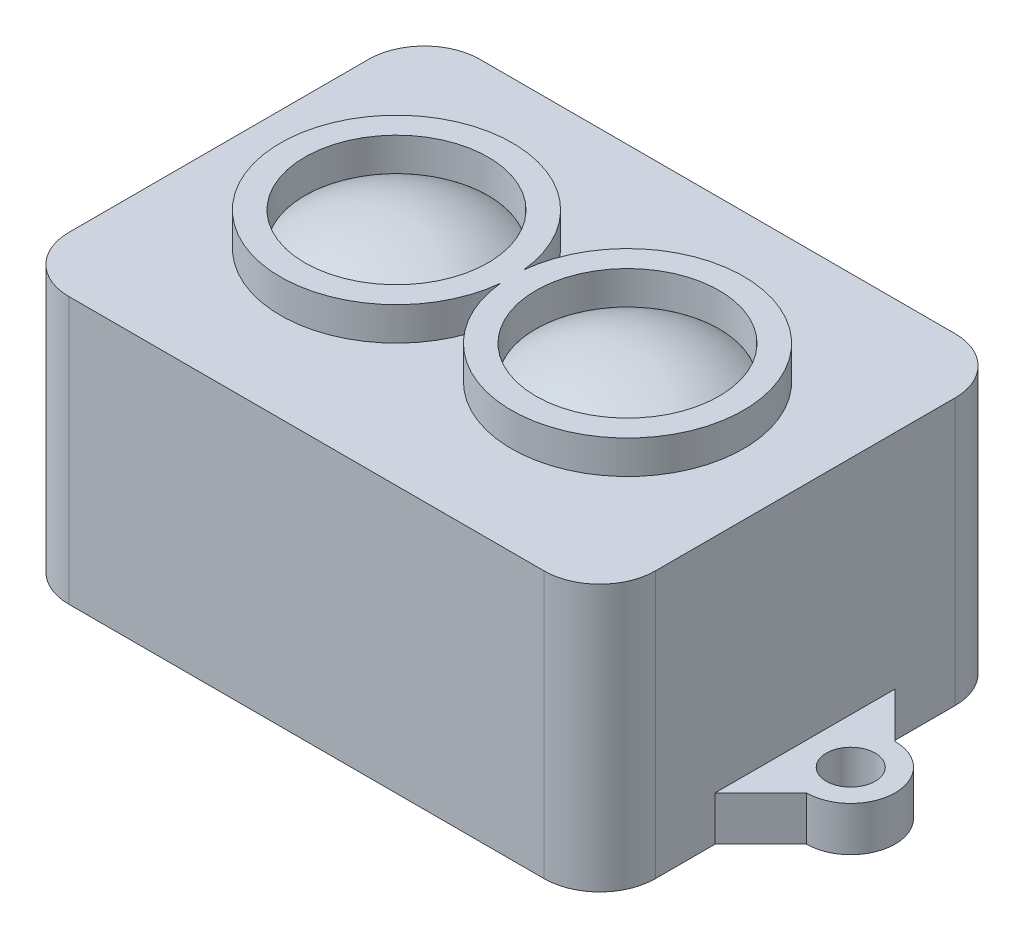
SolidWorks part; units mm, degrees
ref_plane "Front Plane" through (0, 0, 0) normal (0, 0, 1) x (1, 0, 0)
ref_plane "Top Plane" through (0, 0, 0) normal (0, 1, 0) x (1, 0, 0)
ref_plane "Right Plane" through (0, 0, 0) normal (1, 0, 0) x (0, 0, -1)
sketch "Sketch2" plane through (0, 0, 0) normal (0, 1, 0) x (1, 0, 0)
  line L0 (-15.25, 0) -> (15.25, 0) construction
  line L1 (-10.7, -9.25) -> (10.7, -9.25)
  line L2 (-13.2, -6.75) -> (-13.2, -4.05)
  line L3 (-10.7, 9.25) -> (10.7, 9.25)
  line L4 (13.2, -6.75) -> (13.2, -4.05)
  line L5 (-13.2, -9.25) -> (13.2, 9.25) construction
  line L6 (-13.2, 9.25) -> (13.2, -9.25) construction
  line L7 (-15.25, 2) -> (-13.2, 4.05)
  line L8 (-15.25, -2) -> (-13.2, -4.05)
  line L9 (15.25, 2) -> (13.2, 4.05)
  line L10 (15.25, -2) -> (13.2, -4.05)
  line L11 (-10.7, 7.95) -> (10.7, 7.95)
  line L12 (11.9, -6.75) -> (11.9, 6.75)
  line L13 (-10.7, -7.95) -> (10.7, -7.95)
  line L14 (-11.9, -6.75) -> (-11.9, 6.75)
  line L15 (-13.2, 4.05) -> (-13.2, 6.75)
  line L16 (-13.2, -6.75) -> (-13.2, 6.75) construction
  line L17 (13.2, 4.05) -> (13.2, 6.75)
  line L18 (13.2, -6.75) -> (13.2, 6.75) construction
  circle A0 centre (-15.25, 0) radius 1.1
  circle A1 centre (15.25, 0) radius 1.1
  arc A2 (-15.25, 2) -> (-15.25, -2) centre (-15.25, 0) ccw
  arc A3 (15.25, -2) -> (15.25, 2) centre (15.25, 0) ccw
  arc A4 (10.7, -9.25) -> (13.2, -6.75) centre (10.7, -6.75) ccw
  arc A5 (-10.7, -9.25) -> (-13.2, -6.75) centre (-10.7, -6.75) cw
  arc A6 (10.7, 9.25) -> (13.2, 6.75) centre (10.7, 6.75) cw
  arc A7 (-13.2, 6.75) -> (-10.7, 9.25) centre (-10.7, 6.75) cw
  arc A8 (10.7, 7.95) -> (11.9, 6.75) centre (10.7, 6.75) cw
  arc A9 (10.7, -7.95) -> (11.9, -6.75) centre (10.7, -6.75) ccw
  arc A10 (-10.7, -7.95) -> (-11.9, -6.75) centre (-10.7, -6.75) cw
  arc A11 (-11.9, 6.75) -> (-10.7, 7.95) centre (-10.7, 6.75) cw
  point P0 (0, 0)
  point P8 (0, 0)
  dimension "D4" = 2.2
  dimension "D5" = 4
  dimension "D6" = 2.5
  dimension "D1" = 26.4
  dimension "D2" = 18.5
  dimension "D3" = 30.5
  dimension "D7" = 1.3
extrude "Boss-Extrude1" add sketch "Sketch2" along normal blind 2
sketch "Sketch3" plane through (0, 2, 0) normal (0, 1, 0) x (1, 0, 0)
  line L0 (-13.2, 6.75) -> (-13.2, -6.75)
  line L1 (-10.7, 9.25) -> (10.7, 9.25)
  line L2 (-10.7, -9.25) -> (10.7, -9.25)
  line L3 (-10.7, -9.25) -> (10.7, -9.25) construction
  line L4 (13.2, 6.75) -> (13.2, -6.75)
  line L5 (-10.7, 7.95) -> (10.7, 7.95)
  line L6 (11.9, 6.75) -> (11.9, -6.75)
  line L7 (-10.7, -7.95) -> (10.7, -7.95)
  line L8 (-11.9, 6.75) -> (-11.9, -6.75)
  arc A0 (-13.2, 6.75) -> (-10.7, 9.25) centre (-10.7, 6.75) cw
  arc A1 (-13.2, -6.75) -> (-10.7, -9.25) centre (-10.7, -6.75) ccw
  arc A2 (10.7, -9.25) -> (13.2, -6.75) centre (10.7, -6.75) ccw construction
  arc A3 (10.7, -9.25) -> (13.2, -6.75) centre (10.7, -6.75) ccw
  arc A4 (10.7, 9.25) -> (13.2, 6.75) centre (10.7, 6.75) cw
  arc A5 (10.7, 7.95) -> (11.9, 6.75) centre (10.7, 6.75) cw
  arc A6 (10.7, -7.95) -> (11.9, -6.75) centre (10.7, -6.75) ccw
  arc A7 (-11.9, -6.75) -> (-10.7, -7.95) centre (-10.7, -6.75) ccw
  arc A8 (-11.9, 6.75) -> (-10.7, 7.95) centre (-10.7, 6.75) cw
  dimension "D1" = 1.3
extrude "Boss-Extrude2" add sketch "Sketch3" along normal blind 10
sketch "Sketch4" plane through (0, 12, 0) normal (0, 1, 0) x (1, 0, 0)
  line L0 (-10.7, 9.25) -> (10.7, 9.25)
  line L1 (-13.2, 6.75) -> (-13.2, -6.75)
  line L2 (-10.7, -9.25) -> (10.7, -9.25)
  line L3 (13.2, -6.75) -> (13.2, 6.75)
  arc A0 (-10.7, 9.25) -> (-13.2, 6.75) centre (-10.7, 6.75) ccw
  arc A1 (-13.2, -6.75) -> (-10.7, -9.25) centre (-10.7, -6.75) ccw
  arc A2 (10.7, -9.25) -> (13.2, -6.75) centre (10.7, -6.75) ccw
  arc A3 (13.2, 6.75) -> (10.7, 9.25) centre (10.7, 6.75) ccw
extrude "Boss-Extrude3" add sketch "Sketch4" against normal blind 2
sketch "Sketch5" plane through (0, 12, 0) normal (0, 1, 0) x (1, 0, 0)
  line L0 (-5.2, 0) -> (5.2, 0) construction
  circle A0 centre (-5.2, 0) radius 4.125
  circle A1 centre (5.2, 0) radius 4.125
  arc A2 (0, 0.5105) -> (0, -0.5105) centre (-5.2, 0) ccw
  arc A3 (0, -0.5105) -> (0, 0.5105) centre (5.2, 0) ccw
  circle A4 centre (-5.2, 0) radius 5.225 construction
  circle A5 centre (5.2, 0) radius 5.225 construction
  point P2 (0, 0)
  point P3 (0, 0)
  dimension "D2" = 8.25
  dimension "D1" = 10.4
  dimension "D3" = 1.1
extrude "Boss-Extrude4" add sketch "Sketch5" along normal blind 1.5
sketch "Sketch7" plane through (0, 0, 0) normal (0, 0, 1) x (1, 0, 0)
  line L0 (-5.2, 12) -> (-9.325, 12) construction
  line L2 (0, 12) -> (0, 0) construction
  line L3 (-10.7, 0) -> (10.7, 0) construction
  line L4 (-5.2, 13.3) -> (-5.2, 12)
  line L5 (-9.325, 12) -> (-5.2, 12)
  line L6 (-5.2, 13.3) -> (-5.2, 17.7) construction
  arc A0 (-5.2, 13.3) -> (-9.325, 12) centre (-5.2, 6.1055) ccw
  point P0 (-5.2, 13.3)
  point P9 (-20.7, 35.3)
revolve "Revolve1" add sketch "Sketch7" angle 360 about L6
mirror "Mirror1" about plane through (0, 0, 0) normal (1, 0, 0) of bodies 112
